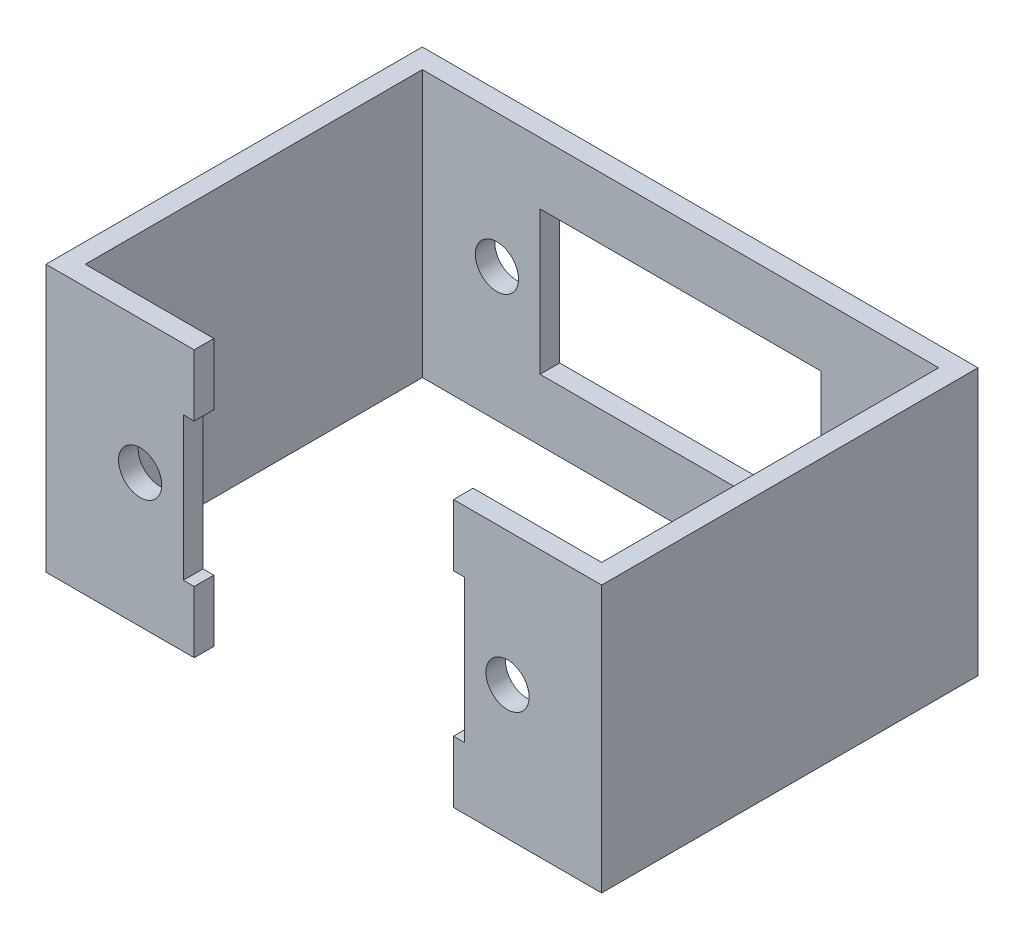
SolidWorks part; units mm, degrees
material "6061 Alloy"
ref_plane "Front Plane" through (0, 0, 0) normal (0, 0, 1) x (1, 0, 0)
ref_plane "Top Plane" through (0, 0, 0) normal (0, 1, 0) x (1, 0, 0)
ref_plane "Right Plane" through (0, 0, 0) normal (1, 0, 0) x (0, 0, -1)
sketch "Sketch2" plane through (0, 0, 0) normal (0, 1, 0) x (1, 0, 0)
  line L0 (-22.5, 0) -> (22.5, 0)
  line L1 (22.5, 0) -> (22.5, -30.48)
  line L2 (22.5, -30.48) -> (10.5, -30.48)
  line L3 (10.5, -30.48) -> (10.5, -28.89)
  line L4 (10.5, -28.89) -> (20.91, -28.89)
  line L5 (20.91, -28.89) -> (20.91, -1.59)
  line L6 (20.91, -1.59) -> (-20.91, -1.59)
  line L7 (-20.91, -1.59) -> (-20.91, -28.89)
  line L8 (-20.91, -28.89) -> (-10.5, -28.89)
  line L9 (-10.5, -28.89) -> (-10.5, -30.48)
  line L10 (-10.5, -30.48) -> (-22.5, -30.48)
  line L11 (-22.5, -30.48) -> (-22.5, 0)
  point P16 (22.5, -15.24)
  point P17 (-16.5, -30.48)
  point P18 (0, 0)
  dimension "D1" = 45
  dimension "D2" = 1.59
  dimension "D3" = 1.59
  dimension "D4" = 1.59
  dimension "D5" = 1.59
  dimension "D6" = 30.48
  dimension "D7" = 12
  dimension "D8" = 12
extrude "Boss-Extrude1" add sketch "Sketch2" along normal blind 21.6
sketch "Sketch3" plane through (0, 0, 30.48) normal (0, 0, 1) x (1, 0, 0)
  line L0 (-22.5, 10.8) -> (22.5, 10.8) construction
  line L1 (-22.5, 21.6) -> (-22.5, 0) construction
  line L2 (22.5, 21.6) -> (22.5, 0) construction
  circle A0 centre (-15, 10.8) radius 1.25
  circle A1 centre (15, 10.8) radius 1.25
  dimension "D1" = 30
  dimension "D3" = 2.5
  dimension "D2" = 15
extrude "Cut-Extrude1" [suppressed] cut sketch "Sketch3" against normal blind 2
sketch "Sketch4" plane through (0, 0, 0) normal (0, 0, -1) x (-1, 0, 0)
  line L0 (-22.5, 10.8) -> (22.5, 10.8) construction
  line L1 (-22.5, 21.6) -> (-22.5, 0) construction
  line L2 (22.5, 21.6) -> (22.5, 0) construction
  line L4 (-11.375, 16.6) -> (11.375, 16.6)
  line L5 (-11.375, 16.6) -> (-11.375, 5)
  line L6 (-11.375, 5) -> (11.375, 5)
  line L7 (11.375, 16.6) -> (11.375, 5)
  line L8 (-11.375, 16.6) -> (11.375, 5) construction
  line L9 (-11.375, 5) -> (11.375, 16.6) construction
  circle A0 centre (-14.875, 10.8) radius 1.75
  circle A1 centre (14.875, 10.8) radius 1.75
  point P6 (0, 10.8)
  dimension "D5" = 3.5
  dimension "D1" = 22.75
  dimension "D2" = 11.6
  dimension "D3" = 3.5
  dimension "D4" = 3.5
extrude "Cut-Extrude2" cut sketch "Sketch4" against normal blind 50
